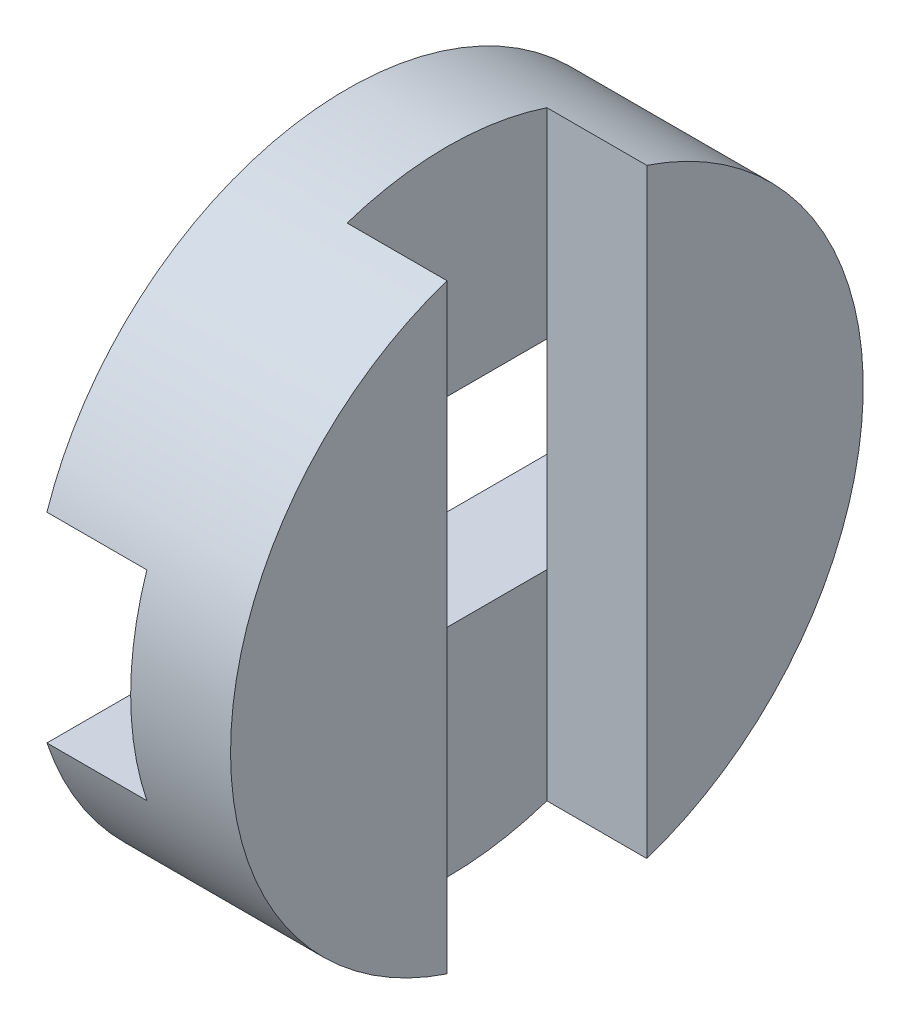
SolidWorks part; units mm, degrees
ref_plane "Plan1" through (0, 0, 0) normal (0, 0, 1) x (1, 0, 0)
ref_plane "Plan2" through (0, 0, 0) normal (0, 1, 0) x (1, 0, 0)
ref_plane "Plan3" through (0, 0, 0) normal (1, 0, 0) x (0, 0, -1)
sketch "Esquisse1" plane through (0, 0, 0) normal (0, 0, 1) x (1, 0, 0)
  line L0 (0, 0) -> (17.6901, 0) construction
  line L2 (0, 0) -> (6, 0)
  line L3 (0, 0) -> (0, 9.5)
  line L4 (0, 9.5) -> (6, 9.5)
  line L5 (6, 0) -> (6, 9.5)
  dimension "D1" = 9.5
  dimension "D2" = 6
revolve "Base-Révolution" add sketch "Esquisse1" angle 360 about L0
sketch "Esquisse2" plane through (0, 0, 0) normal (0, 0, 1) x (1, 0, 0)
  line L0 (-1.7667, 0) -> (3.4211, 0) construction
  line L1 (0, 3) -> (3, 3)
  line L2 (0, 3) -> (0, -3)
  line L3 (0, -3) -> (3, -3)
  line L4 (3, 3) -> (3, -3)
  line L5 (0, 0) -> (17.6901, 0) construction
  line L6 (0, 9.5) -> (0, -9.5) construction
  dimension "D1" = 3
  dimension "D2" = 6
extrude "Enlèv. mat.-Extru.1" cut sketch "Esquisse2" against normal mid plane 20
sketch "Esquisse3" plane through (0, 0, 0) normal (0, 1, 0) x (1, 0, 0)
  line L0 (0, 0) -> (7.1604, 0) construction
  line L1 (6, 3) -> (3, 3)
  line L2 (6, 3) -> (6, -3)
  line L3 (6, -3) -> (3, -3)
  line L4 (3, 3) -> (3, -3)
  line L5 (0, 0) -> (17.6901, 0) construction
  line L6 (6, -9.5) -> (6, 9.5) construction
  dimension "D1" = 3
  dimension "D2" = 6
extrude "Enlèv. mat.-Extru.2" cut sketch "Esquisse3" against normal mid plane 20
